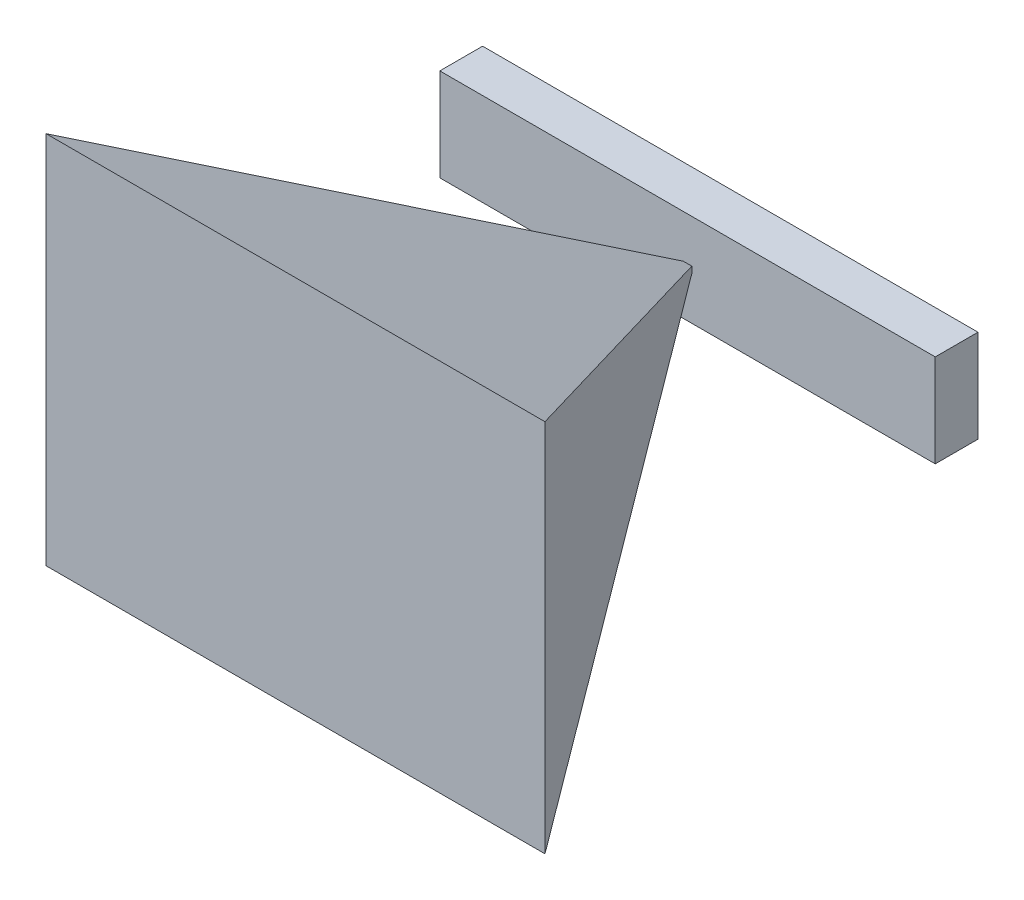
SolidWorks part; units mm, degrees
material "6061 合金"
ref_plane "前视基准面" through (0, 0, 0) normal (0, 0, 1) x (1, 0, 0)
ref_plane "上视基准面" through (0, 0, 0) normal (0, 1, 0) x (1, 0, 0)
ref_plane "右视基准面" through (0, 0, 0) normal (1, 0, 0) x (0, 0, -1)
sketch "草图1" plane through (0, 0, 0) normal (0, 0, 1) x (1, 0, 0)
  line L1 (-69.5, -13) -> (69.5, -13)
  line L2 (-69.5, -13) -> (-69.5, 13)
  line L3 (-69.5, 13) -> (69.5, 13)
  line L4 (69.5, -13) -> (69.5, 13)
  line L5 (-69.5, -13) -> (69.5, 13) construction
  line L6 (-69.5, 13) -> (69.5, -13) construction
  point P0 (0, 0)
  dimension "D1" = 139
  dimension "D2" = 26
extrude "凸台-拉伸1" add sketch "草图1" along normal blind 12
sketch "草图2" plane through (0, 0, 0) normal (0, 0, -1) x (-1, 0, 0)
  line L0 (0, 13) -> (0, -13) construction
  line L1 (-69.5, 13) -> (69.5, 13) construction
  line L2 (69.5, -13) -> (-69.5, -13) construction
  line L3 (-25, 0) -> (0, 0) construction
  circle A0 centre (-25, 0) radius 1.2
  circle A1 centre (25, 0) radius 1.2
  dimension "D1" = 2.4
  dimension "D2" = 50
extrude "切除-拉伸1" cut sketch "草图2" against normal blind 5
cosmetic thread "装饰螺纹线1" parameters "D2"=3
cosmetic thread "装饰螺纹线2" parameters "D2"=3
ref_point " "
sketch "草图3" plane through (0, 0, 12) normal (0, 0, 1) x (1, 0, 0)
  circle A0 centre (10, 0) radius 4.6116
  dimension "D1" = 10
ref_plane "基准面1" through (0, 0, 122) normal (0, 0, 1) x (1, 0, 0)
sketch "草图4" plane through (0, 0, 122) normal (0, 0, 1) x (1, 0, 0)
  line L1 (-70, -52.5) -> (70, -52.5)
  line L2 (-70, -52.5) -> (-70, 52.5)
  line L3 (-70, 52.5) -> (70, 52.5)
  line L4 (70, -52.5) -> (70, 52.5)
  line L5 (-70, -52.5) -> (70, 52.5) construction
  line L6 (-70, 52.5) -> (70, -52.5) construction
  point P0 (0, 0)
  dimension "D1" = 140
  dimension "D2" = 105
sketch "草图5" plane through (0, 0, 12) normal (0, 0, 1) x (1, 0, 0)
  line L0 (-70, 52.5) -> (70, -52.5) construction
  line L1 (-1.2, -0.9) -> (1.2, -0.9)
  line L2 (-1.2, -0.9) -> (-1.2, 0.9)
  line L3 (-1.2, 0.9) -> (1.2, 0.9)
  line L4 (1.2, -0.9) -> (1.2, 0.9)
  line L5 (-1.2, -0.9) -> (1.2, 0.9) construction
  line L6 (-1.2, 0.9) -> (1.2, -0.9) construction
  point P0 (0, 0)
  dimension "D1" = 1.8
  dimension "D2" = 2.4
loft "放样1" add profiles "草图5", "草图4"
